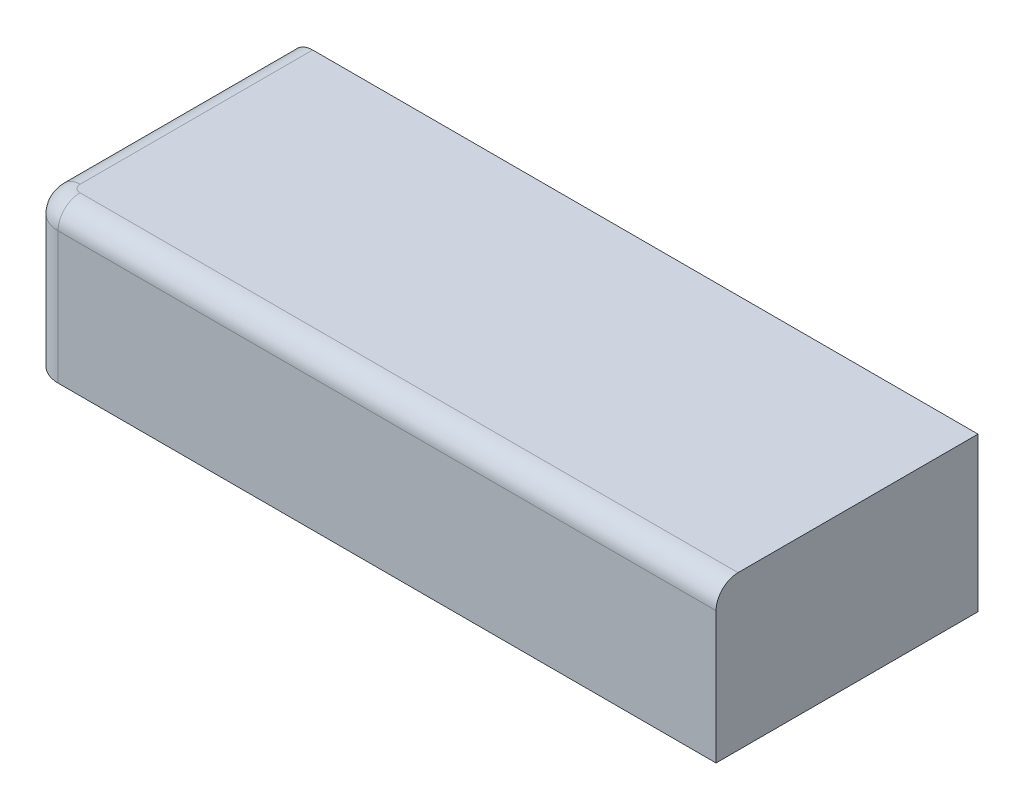
SolidWorks part; units mm, degrees
ref_plane "Front" through (0, 0, 0) normal (0, 0, 1) x (1, 0, 0)
ref_plane "Top" through (0, 0, 0) normal (0, 1, 0) x (1, 0, 0)
ref_plane "Right" through (0, 0, 0) normal (1, 0, 0) x (0, 0, -1)
other "Configuration Table"
sketch "Sketch1" plane through (0, 0, 0) normal (0, 1, 0) x (1, 0, 0)
  line L1 (-46.9, 17.875) -> (46.9, 17.875)
  line L2 (-46.9, 17.875) -> (-46.9, -13.875)
  line L3 (-42.9, -17.875) -> (46.9, -17.875)
  line L4 (46.9, 17.875) -> (46.9, -17.875)
  line L5 (-46.9, 17.875) -> (46.9, -17.875) construction
  line L6 (-46.9, -17.875) -> (46.9, 17.875) construction
  arc A0 (-46.9, -13.875) -> (-42.9, -17.875) centre (-42.9, -13.875) ccw
  point P0 (0, 0)
  dimension "D3" = 4
  dimension "D1" = 93.8
  dimension "D2" = 35.75
extrude "Boss-Extrude1" add sketch "Sketch1" along normal blind 21
fillet "Fillet1" radius 3 3 edges at (-46.9, 21, -2) (2, 21, 17.875) (-45.7284, 21, 16.7034)
